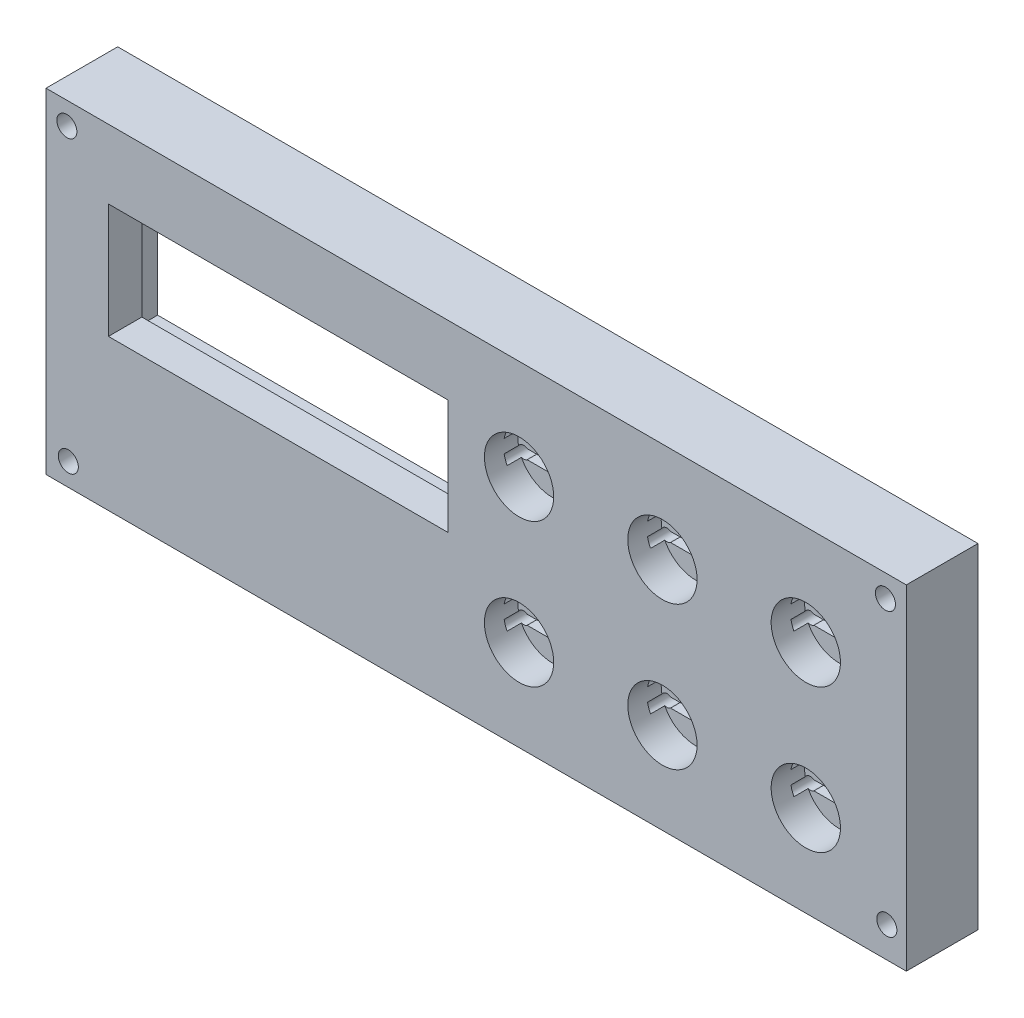
SolidWorks part; units mm, degrees
ref_plane "前视基准面" through (0, 0, 0) normal (0, 0, 1) x (1, 0, 0)
ref_plane "上视基准面" through (0, 0, 0) normal (0, 1, 0) x (1, 0, 0)
ref_plane "右视基准面" through (0, 0, 0) normal (1, 0, 0) x (0, 0, -1)
sketch "草图1" plane through (0, 0, 0) normal (0, 0, 1) x (1, 0, 0)
  line L1 (0, 0) -> (180, 0)
  line L2 (0, 0) -> (0, 70)
  line L3 (0, 70) -> (180, 70)
  line L4 (180, 0) -> (180, 70)
  dimension "D1" = 180
  dimension "D2" = 70
extrude "凸台-拉伸1" add sketch "草图1" along normal blind 15
sketch "草图2" plane through (0, 0, 15) normal (0, 0, 1) x (1, 0, 0)
  line L0 (90, 70) -> (90, 0) construction
  line L1 (13.0587, 55.5554) -> (84.0587, 55.5554)
  line L2 (13.0587, 55.5554) -> (13.0587, 31.5554)
  line L3 (13.0587, 31.5554) -> (84.0587, 31.5554)
  line L4 (84.0587, 55.5554) -> (84.0587, 31.5554)
  line L5 (180, 70) -> (0, 70) construction
  line L6 (0, 0) -> (180, 0) construction
  line L7 (0, 35) -> (180, 35.8878) construction
  line L8 (0, 70) -> (0, 0) construction
  line L9 (180, 0) -> (180, 70) construction
  circle A0 centre (4.3675, 65.3253) radius 2.1
  circle A1 centre (175.6325, 65.3253) radius 2.1
  circle A2 centre (175.9231, 6.4086) radius 2.1
  circle A3 centre (4.6664, 4.7192) radius 2.1
  dimension "D3" = 4.2
  dimension "D1" = 71
  dimension "D2" = 24
extrude "切除-拉伸1" cut sketch "草图2" against normal through all
sketch "草图5" plane through (0, 0, 0) normal (0, 0, -1) x (-1, 0, 0)
  line L0 (-48.5587, 55.5554) -> (-48.5587, 31.5554) construction
  line L5 (-84.0587, 55.5554) -> (-13.0587, 55.5554)
  line L10 (-84.0587, 43.5554) -> (-13.0587, 43.5554) construction
  line L12 (-84.0587, 55.5554) -> (-84.0587, 31.5554)
  line L13 (-84.0587, 31.5554) -> (-13.0587, 31.5554)
  line L14 (-13.0587, 55.5554) -> (-13.0587, 31.5554)
  line L15 (-88.7587, 61.5554) -> (-8.3587, 61.5554)
  line L16 (-88.7587, 61.5554) -> (-88.7587, 25.5554)
  line L17 (-88.7587, 25.5554) -> (-8.3587, 25.5554)
  line L18 (-8.3587, 61.5554) -> (-8.3587, 25.5554)
  dimension "D1" = 80.4
  dimension "D2" = 36
extrude "切除-拉伸3" cut sketch "草图5" against normal blind 8
sketch "草图6" plane through (0, 0, 8) normal (0, 0, -1) x (-1, 0, 0)
  line L0 (-88.7587, 61.5554) -> (-88.7587, 25.5554) construction
  line L1 (-84.0587, 55.5554) -> (-88.7587, 55.5554)
  line L2 (-84.0587, 55.5554) -> (-84.0587, 31.5554)
  line L3 (-84.0587, 31.5554) -> (-88.7587, 31.5554)
  line L4 (-88.7587, 55.5554) -> (-88.7587, 31.5554)
extrude "切除-拉伸4" cut sketch "草图6" against normal blind 3
sketch "草图7" plane through (0, 0, 15) normal (0, 0, 1) x (1, 0, 0)
  circle A0 centre (98.9728, 49.0677) radius 7.25
  circle A1 centre (128.9728, 49.0677) radius 7.25
  circle A2 centre (158.9728, 49.0677) radius 7.25
  circle A3 centre (128.9728, 19.0677) radius 7.25
  circle A4 centre (158.9728, 19.0677) radius 7.25
  circle A5 centre (98.9728, 19.0677) radius 7.25
  dimension "D1" = 14.5
  dimension "D2" = 3
  dimension "D3" = 2
extrude "切除-拉伸5" cut sketch "草图7" against normal blind 7
sketch "草图8" plane through (0, 0, 8) normal (0, 0, 1) x (1, 0, 0)
  line L0 (98.9728, 56.3177) -> (98.9728, 41.8177) construction
  line L1 (91.7228, 49.0677) -> (106.2228, 49.0677) construction
  line L2 (95.9228, 48.0177) -> (92.9228, 48.0177)
  line L3 (95.9228, 52.1177) -> (102.0228, 52.1177)
  line L4 (95.9228, 50.1177) -> (95.9228, 48.0177)
  line L5 (95.9228, 46.0177) -> (102.0228, 46.0177)
  line L6 (102.0228, 50.1177) -> (102.0228, 48.0177)
  line L7 (95.9228, 52.1177) -> (92.9228, 52.1177)
  line L9 (95.9228, 50.1177) -> (92.9228, 50.1177)
  line L10 (92.9228, 52.1177) -> (92.9228, 50.1177)
  line L11 (95.9228, 46.0177) -> (92.9228, 46.0177)
  line L12 (92.9228, 46.0177) -> (92.9228, 48.0177)
  line L13 (102.0228, 46.0177) -> (105.0228, 46.0177)
  line L14 (105.0228, 46.0177) -> (105.0228, 48.0177)
  line L15 (102.0228, 48.0177) -> (105.0228, 48.0177)
  line L16 (105.0228, 52.1177) -> (105.0228, 50.1177)
  line L17 (102.0228, 52.1177) -> (105.0228, 52.1177)
  line L18 (102.0228, 50.1177) -> (105.0228, 50.1177)
  line L19 (125.9228, 52.1177) -> (132.0228, 52.1177)
  line L20 (132.0228, 52.1177) -> (135.0228, 52.1177)
  line L21 (135.0228, 52.1177) -> (135.0228, 50.1177)
  line L22 (132.0228, 50.1177) -> (135.0228, 50.1177)
  line L23 (132.0228, 50.1177) -> (132.0228, 48.0177)
  line L24 (132.0228, 48.0177) -> (135.0228, 48.0177)
  line L25 (135.0228, 46.0177) -> (135.0228, 48.0177)
  line L26 (132.0228, 46.0177) -> (135.0228, 46.0177)
  line L27 (125.9228, 46.0177) -> (132.0228, 46.0177)
  line L28 (125.9228, 46.0177) -> (122.9228, 46.0177)
  line L29 (122.9228, 46.0177) -> (122.9228, 48.0177)
  line L30 (125.9228, 48.0177) -> (122.9228, 48.0177)
  line L31 (125.9228, 50.1177) -> (125.9228, 48.0177)
  line L32 (125.9228, 50.1177) -> (122.9228, 50.1177)
  line L33 (122.9228, 52.1177) -> (122.9228, 50.1177)
  line L34 (125.9228, 52.1177) -> (122.9228, 52.1177)
  line L35 (155.9228, 52.1177) -> (162.0228, 52.1177)
  line L36 (162.0228, 52.1177) -> (165.0228, 52.1177)
  line L37 (165.0228, 52.1177) -> (165.0228, 50.1177)
  line L38 (162.0228, 50.1177) -> (165.0228, 50.1177)
  line L39 (162.0228, 50.1177) -> (162.0228, 48.0177)
  line L40 (162.0228, 48.0177) -> (165.0228, 48.0177)
  line L41 (165.0228, 46.0177) -> (165.0228, 48.0177)
  line L42 (162.0228, 46.0177) -> (165.0228, 46.0177)
  line L43 (155.9228, 46.0177) -> (162.0228, 46.0177)
  line L44 (155.9228, 46.0177) -> (152.9228, 46.0177)
  line L45 (152.9228, 46.0177) -> (152.9228, 48.0177)
  line L46 (155.9228, 48.0177) -> (152.9228, 48.0177)
  line L47 (155.9228, 50.1177) -> (155.9228, 48.0177)
  line L48 (155.9228, 50.1177) -> (152.9228, 50.1177)
  line L49 (152.9228, 52.1177) -> (152.9228, 50.1177)
  line L50 (155.9228, 52.1177) -> (152.9228, 52.1177)
  line L51 (125.9228, 22.1177) -> (132.0228, 22.1177)
  line L52 (132.0228, 22.1177) -> (135.0228, 22.1177)
  line L53 (135.0228, 22.1177) -> (135.0228, 20.1177)
  line L54 (132.0228, 20.1177) -> (135.0228, 20.1177)
  line L55 (132.0228, 20.1177) -> (132.0228, 18.0177)
  line L56 (132.0228, 18.0177) -> (135.0228, 18.0177)
  line L57 (135.0228, 16.0177) -> (135.0228, 18.0177)
  line L58 (132.0228, 16.0177) -> (135.0228, 16.0177)
  line L59 (125.9228, 16.0177) -> (132.0228, 16.0177)
  line L60 (125.9228, 16.0177) -> (122.9228, 16.0177)
  line L61 (122.9228, 16.0177) -> (122.9228, 18.0177)
  line L62 (125.9228, 18.0177) -> (122.9228, 18.0177)
  line L63 (125.9228, 20.1177) -> (125.9228, 18.0177)
  line L64 (125.9228, 20.1177) -> (122.9228, 20.1177)
  line L65 (122.9228, 22.1177) -> (122.9228, 20.1177)
  line L66 (125.9228, 22.1177) -> (122.9228, 22.1177)
  line L67 (155.9228, 22.1177) -> (162.0228, 22.1177)
  line L68 (162.0228, 22.1177) -> (165.0228, 22.1177)
  line L69 (165.0228, 22.1177) -> (165.0228, 20.1177)
  line L70 (162.0228, 20.1177) -> (165.0228, 20.1177)
  line L71 (162.0228, 20.1177) -> (162.0228, 18.0177)
  line L72 (162.0228, 18.0177) -> (165.0228, 18.0177)
  line L73 (165.0228, 16.0177) -> (165.0228, 18.0177)
  line L74 (162.0228, 16.0177) -> (165.0228, 16.0177)
  line L75 (155.9228, 16.0177) -> (162.0228, 16.0177)
  line L76 (155.9228, 16.0177) -> (152.9228, 16.0177)
  line L77 (152.9228, 16.0177) -> (152.9228, 18.0177)
  line L78 (155.9228, 18.0177) -> (152.9228, 18.0177)
  line L79 (155.9228, 20.1177) -> (155.9228, 18.0177)
  line L80 (155.9228, 20.1177) -> (152.9228, 20.1177)
  line L81 (152.9228, 22.1177) -> (152.9228, 20.1177)
  line L82 (155.9228, 22.1177) -> (152.9228, 22.1177)
  line L83 (95.9228, 22.1177) -> (102.0228, 22.1177)
  line L84 (102.0228, 22.1177) -> (105.0228, 22.1177)
  line L85 (105.0228, 22.1177) -> (105.0228, 20.1177)
  line L86 (102.0228, 20.1177) -> (105.0228, 20.1177)
  line L87 (102.0228, 20.1177) -> (102.0228, 18.0177)
  line L88 (102.0228, 18.0177) -> (105.0228, 18.0177)
  line L89 (105.0228, 16.0177) -> (105.0228, 18.0177)
  line L90 (102.0228, 16.0177) -> (105.0228, 16.0177)
  line L91 (95.9228, 16.0177) -> (102.0228, 16.0177)
  line L92 (95.9228, 16.0177) -> (92.9228, 16.0177)
  line L93 (92.9228, 16.0177) -> (92.9228, 18.0177)
  line L94 (95.9228, 18.0177) -> (92.9228, 18.0177)
  line L95 (95.9228, 20.1177) -> (95.9228, 18.0177)
  line L96 (95.9228, 20.1177) -> (92.9228, 20.1177)
  line L97 (92.9228, 22.1177) -> (92.9228, 20.1177)
  line L98 (95.9228, 22.1177) -> (92.9228, 22.1177)
  circle A0 centre (98.9728, 49.0677) radius 7.25 construction
  circle A1 centre (98.9728, 49.0677) radius 7.25 construction
  dimension "D1" = 6.1
  dimension "D2" = 6.1
  dimension "D3" = 2
  dimension "D4" = 3
  dimension "D5" = 3
  dimension "D6" = 2
extrude "切除-拉伸6" cut sketch "草图8" against normal blind 4.2
sketch "草图9" plane through (0, 0, 8) normal (0, 0, 1) x (1, 0, 0)
  line L0 (92.9228, 52.1177) -> (92.9228, 50.1177) construction
  line L1 (98.9728, 52.1177) -> (98.9728, 46.0177) construction
  line L2 (105.0228, 52.1177) -> (92.9228, 52.1177) construction
  line L3 (92.9228, 46.0177) -> (105.0228, 46.0177) construction
  line L4 (95.9228, 49.0677) -> (102.0228, 49.0677) construction
  line L5 (95.9228, 50.1177) -> (95.9228, 48.0177) construction
  line L6 (102.0228, 48.0177) -> (102.0228, 50.1177) construction
  circle A0 centre (92.9228, 51.1177) radius 1.25
  circle A1 centre (105.0228, 51.1177) radius 1.25
  circle A2 centre (105.0228, 47.0177) radius 1.25
  circle A3 centre (92.9228, 47.0177) radius 1.25
  circle A4 centre (122.9228, 51.1177) radius 1.25
  circle A5 centre (135.0228, 51.1177) radius 1.25
  circle A6 centre (135.0228, 47.0177) radius 1.25
  circle A7 centre (122.9228, 47.0177) radius 1.25
  circle A8 centre (152.9228, 51.1177) radius 1.25
  circle A9 centre (165.0228, 51.1177) radius 1.25
  circle A10 centre (165.0228, 47.0177) radius 1.25
  circle A11 centre (152.9228, 47.0177) radius 1.25
  circle A12 centre (122.9228, 21.1177) radius 1.25
  circle A13 centre (135.0228, 21.1177) radius 1.25
  circle A14 centre (135.0228, 17.0177) radius 1.25
  circle A15 centre (122.9228, 17.0177) radius 1.25
  circle A16 centre (152.9228, 21.1177) radius 1.25
  circle A17 centre (165.0228, 21.1177) radius 1.25
  circle A18 centre (165.0228, 17.0177) radius 1.25
  circle A19 centre (152.9228, 17.0177) radius 1.25
  circle A20 centre (92.9228, 21.1177) radius 1.25
  circle A21 centre (105.0228, 21.1177) radius 1.25
  circle A22 centre (105.0228, 17.0177) radius 1.25
  circle A23 centre (92.9228, 17.0177) radius 1.25
  dimension "D1" = 2.5
  dimension "D2" = 3
  dimension "D3" = 2
extrude "切除-拉伸7" cut sketch "草图9" against normal through all and the other way blind 3
sketch "草图10" plane through (0, 0, 0) normal (0, 0, -1) x (-1, 0, 0)
  line L0 (-171.0022, 67.4692) -> (-9.1345, 67.4692)
  line L1 (-9.1345, 67.4692) -> (-9.1345, 64.3249)
  line L2 (-9.1345, 64.3249) -> (-92.2558, 64.3249)
  line L3 (-92.2558, 64.3249) -> (-92.2558, 58.5829)
  line L4 (-92.2558, 58.5829) -> (-168.4047, 58.5829)
  line L5 (-168.4047, 58.5829) -> (-168.4047, 10.3234)
  line L6 (-168.4047, 10.3234) -> (-88.5645, 10.3234)
  line L7 (-88.5645, 10.3234) -> (-88.5645, 21.8072)
  line L8 (-88.5645, 21.8072) -> (-6.537, 21.8072)
  line L9 (-3.1191, 21.8072) -> (-3.1191, 10.3234)
  line L10 (-3.1191, 10.3234) -> (-10.2282, 10.3234)
  line L11 (-10.2282, 10.3234) -> (-10.2282, 3.2143)
  line L12 (-10.2282, 3.2143) -> (-171.0022, 3.2143)
  line L13 (-171.0022, 3.2143) -> (-171.0022, 10.3234)
  line L14 (-171.0022, 10.3234) -> (-177.1543, 10.3234)
  line L15 (-177.1543, 10.3234) -> (-177.1543, 58.5829)
  line L16 (-177.1543, 58.5829) -> (-171.0022, 58.5829)
  line L17 (-171.0022, 58.5829) -> (-171.0022, 67.4692)
  line L18 (-3.1191, 21.8072) -> (-3.1191, 60.6336)
  line L19 (-3.1191, 60.6336) -> (-6.537, 60.6336)
  line L20 (-6.537, 60.6336) -> (-6.537, 21.8072)
extrude "切除-拉伸8" cut sketch "草图10" against normal blind 13
sketch "草图11" plane through (0, 0, 0) normal (0, 0, -1) x (-1, 0, 0)
  line L0 (-168.4047, 58.5829) -> (-92.2558, 58.5829) construction
  line L1 (-148.1645, 58.5829) -> (-139.299, 58.5829)
  line L2 (-148.1645, 58.5829) -> (-148.1645, 39.7286)
  line L3 (-148.1645, 10.3234) -> (-139.299, 10.3234)
  line L4 (-139.299, 58.5829) -> (-139.299, 39.7286)
  line L5 (-88.5645, 10.3234) -> (-168.4047, 10.3234) construction
  line L6 (-168.4047, 10.3234) -> (-168.4047, 58.5829) construction
  line L7 (-118.2843, 58.5829) -> (-109.1999, 58.5829)
  line L8 (-118.2843, 58.5829) -> (-118.2843, 39.7286)
  line L9 (-118.2843, 10.3234) -> (-109.1999, 10.3234)
  line L10 (-109.1999, 58.5829) -> (-109.1999, 39.7286)
  line L11 (-168.4047, 39.7286) -> (-148.1645, 39.7286)
  line L12 (-168.4047, 39.7286) -> (-168.4047, 28.674)
  line L13 (-168.4047, 28.674) -> (-148.1645, 28.674)
  line L14 (-91.031, 39.7286) -> (-91.031, 28.674)
  line L15 (-148.1645, 28.674) -> (-148.1645, 10.3234)
  line L16 (-139.299, 28.674) -> (-139.299, 10.3234)
  line L17 (-118.2843, 28.674) -> (-118.2843, 10.3234)
  line L18 (-109.1999, 28.674) -> (-109.1999, 10.3234)
  line L19 (-109.1999, 39.7286) -> (-91.031, 39.7286)
  line L20 (-109.1999, 28.674) -> (-91.031, 28.674)
  line L21 (-139.299, 39.7286) -> (-118.2843, 39.7286)
  line L22 (-139.299, 28.674) -> (-118.2843, 28.674)
extrude "切除-拉伸10" cut sketch "草图11" against normal blind 12
